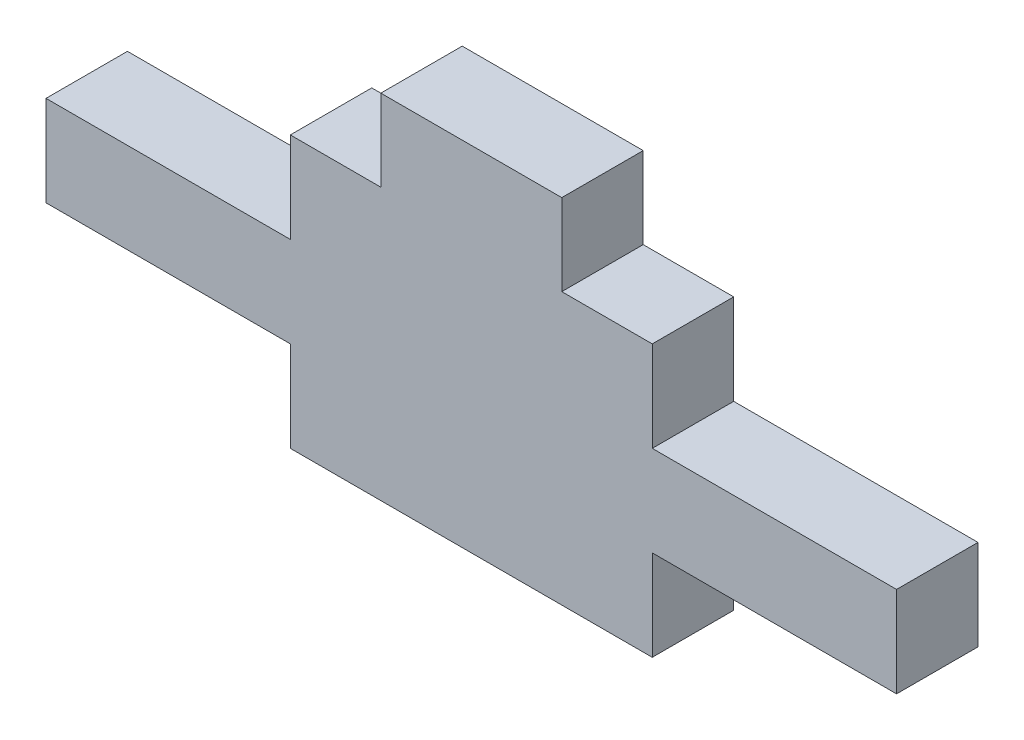
SolidWorks part; units mm, degrees
ref_plane "Front Plane" through (0, 0, 0) normal (0, 0, 1) x (1, 0, 0)
ref_plane "Top Plane" through (0, 0, 0) normal (0, 1, 0) x (1, 0, 0)
ref_plane "Right Plane" through (0, 0, 0) normal (1, 0, 0) x (0, 0, -1)
sketch "Model" plane through (0, 0, 0) normal (0, 0, 1) x (1, 0, 0)
  line L16 (0, 0) -> (0, 39) construction
  line L18 (-20, 0) -> (20, 0)
  line L19 (-20, 0) -> (-20, 10)
  line L20 (-20, 30) -> (-10, 30)
  line L21 (20, 0) -> (20, 10)
  line L22 (47, 20) -> (47, 10)
  line L23 (-10, 30) -> (-10, 39)
  line L24 (-10, 39) -> (10, 39)
  line L25 (10, 30) -> (10, 39)
  line L26 (10, 30) -> (20, 30)
  line L27 (-20, 20) -> (-47, 20)
  line L28 (20, 20) -> (20, 30)
  line L29 (-20, 10) -> (-47, 10)
  line L30 (-47, 20) -> (-47, 10)
  line L31 (20, 10) -> (47, 10)
  line L33 (20, 20) -> (47, 20)
  line L34 (-20, 20) -> (-20, 30)
  point P30 (0, 39)
  dimension "D3" = 40
  dimension "D4" = 30
  dimension "D5" = 9
  dimension "D7" = 20
  dimension "D9" = 27
  dimension "D11" = 10
extrude "Boss-Extrude1" add sketch "Model" along normal blind 9
equation "\"material-thickness\"= 9mm"
equation "\"tab-width-small\"= 20mm ' Width of the small version of the Tab"
equation "\"plate-supporttab-gapwidth\"= 40mm"
equation "\"D5@Model\"=\"material-thickness\""
equation "\"D1@Boss-Extrude1\"=\"material-thickness\""
equation "\"D9@Model\"=\"material-thickness\"*3"
equation "\"D7@Model\"=\"tab-width-small\""
equation "\"D3@Model\"=\"plate-supporttab-gapwidth\""
